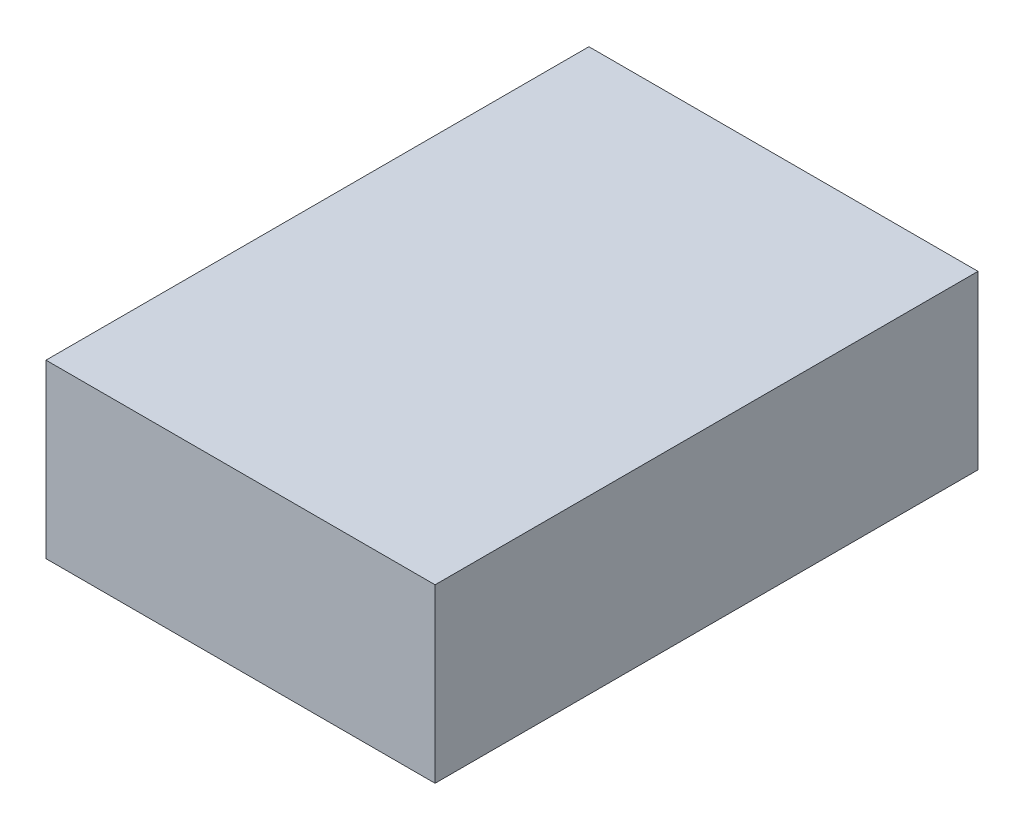
SolidWorks part; units mm, degrees
ref_plane "Front Plane" through (0, 0, 0) normal (0, 0, 1) x (1, 0, 0)
ref_plane "Top Plane" through (0, 0, 0) normal (0, 1, 0) x (1, 0, 0)
ref_plane "Right Plane" through (0, 0, 0) normal (1, 0, 0) x (0, 0, -1)
sketch "Sketch1" plane through (0, 0, 0) normal (0, 1, 0) x (1, 0, 0)
  line L0 (-27.305, 38.1) -> (27.305, -38.1) construction
  line L1 (-27.305, 38.1) -> (27.305, 38.1)
  line L2 (-27.305, 38.1) -> (-27.305, -38.1)
  line L3 (-27.305, -38.1) -> (27.305, -38.1)
  line L4 (27.305, 38.1) -> (27.305, -38.1)
  dimension "D1" = 54.61
  dimension "D2" = 76.2
extrude "Boss-Extrude1" add sketch "Sketch1" along normal mid plane 24.13
